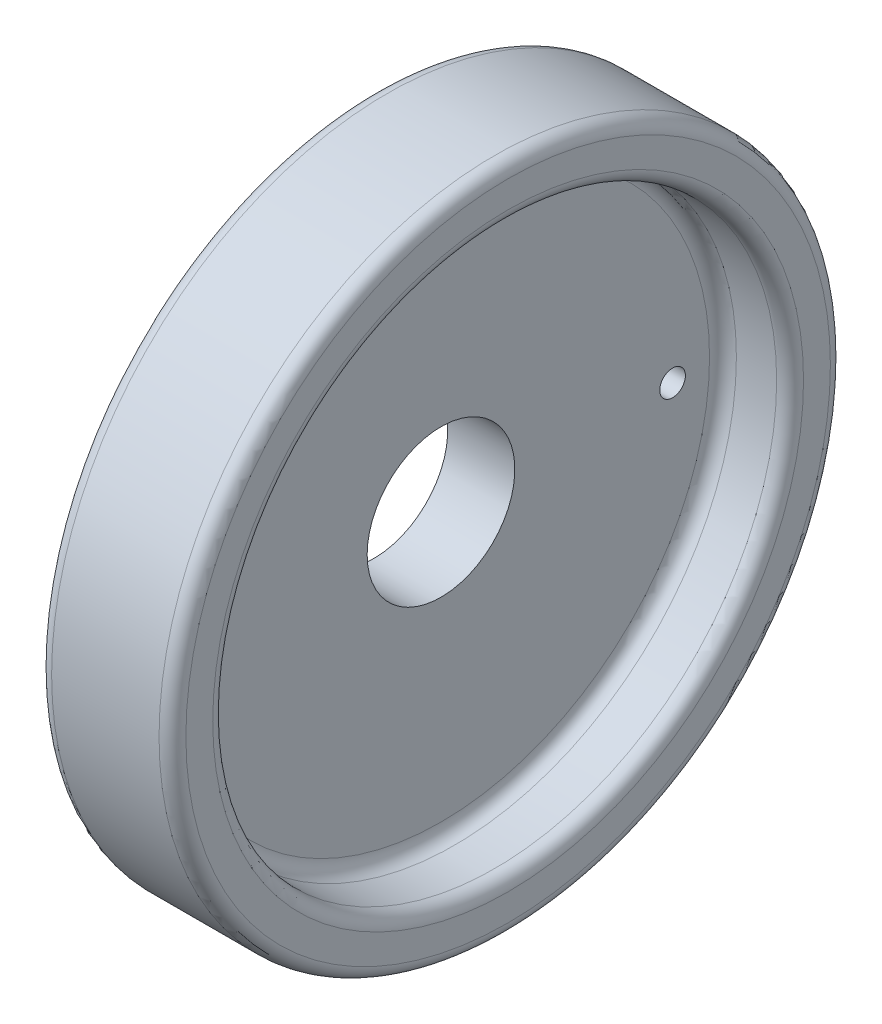
SolidWorks part; units mm, degrees
ref_plane "Front Plane" through (0, 0, 0) normal (0, 0, 1) x (1, 0, 0)
ref_plane "Top Plane" through (0, 0, 0) normal (0, 1, 0) x (1, 0, 0)
ref_plane "Right Plane" through (0, 0, 0) normal (1, 0, 0) x (0, 0, -1)
sketch "Sketch2" plane through (0, 0, 0) normal (0, 0, 1) x (1, 0, 0)
  line L0 (0, 0) -> (0, 2.75) construction
  line L1 (0, 2.75) -> (0, 12)
  line L2 (0.5, 12.5) -> (4.5, 12.5)
  line L3 (5, 12) -> (5, 11)
  line L5 (4.5, 10.5) -> (3, 10.5)
  line L9 (2.5, 10) -> (2.5, 2.75)
  line L10 (2.5, 2.75) -> (0, 2.75)
  line L11 (0, 0) -> (2.5, 0) construction
  arc A0 (0.5, 12.5) -> (0, 12) centre (0.5, 12) ccw
  arc A1 (3, 10.5) -> (2.5, 10) centre (3, 10) ccw
  arc A2 (5, 11) -> (4.5, 10.5) centre (4.5, 11) cw
  arc A3 (4.5, 12.5) -> (5, 12) centre (4.5, 12) cw
  point P10 (0, 12.5)
  point P17 (5, 12.5)
  dimension "D5" = 0.5
  dimension "D1" = 5
  dimension "D2" = 2.75
  dimension "D3" = 2
  dimension "D4" = 12.5
  dimension "D6" = 2.5
revolve "Revolve1" add sketch "Sketch2" angle 360 about L11
sketch "Sketch3" plane through (5, 0, 0) normal (1, 0, 0) x (0, 0, -1)
  circle A0 centre (0, 0) radius 12.5 construction
  circle A1 centre (0, 0) radius 12.5
sketch "Sketch4" plane through (2.5, 0, 0) normal (1, 0, 0) x (0, 0, -1)
  circle A0 centre (8.6233, -0.1479) radius 0.4778
extrude "Cut-Extrude1" cut sketch "Sketch4" against normal up to next
